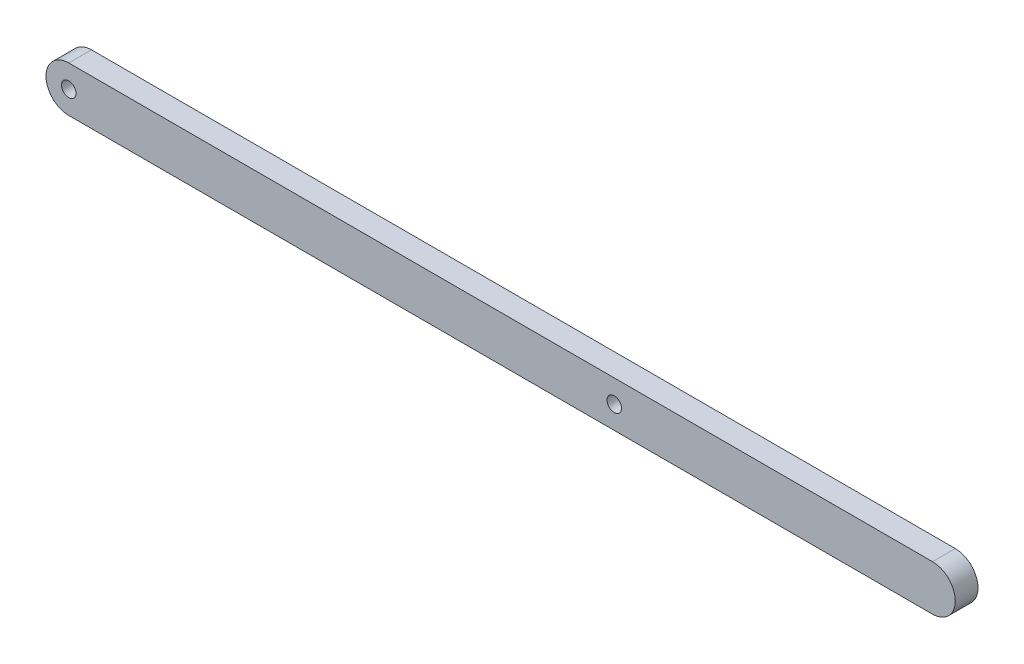
SolidWorks part; units mm, degrees
ref_plane "前视基准面" through (0, 0, 0) normal (0, 0, 1) x (1, 0, 0)
ref_plane "上视基准面" through (0, 0, 0) normal (0, 1, 0) x (1, 0, 0)
ref_plane "右视基准面" through (0, 0, 0) normal (1, 0, 0) x (0, 0, -1)
other "Configuration Table"
sketch "草图1" plane through (0, 0, 0) normal (0, 0, 1) x (1, 0, 0)
  line L0 (0, 0) -> (190, 0) construction
  line L1 (0, 5) -> (190, 5)
  line L2 (0, -5) -> (190, -5)
  arc A0 (0, 5) -> (0, -5) centre (0, 0) ccw
  arc A1 (190, -5) -> (190, 5) centre (190, 0) ccw
  circle A2 centre (120, 0) radius 1.6
  circle A3 centre (0, 0) radius 1.6
  point P3 (95, 0)
  dimension "D3" = 3.2
  dimension "D5" = 3.2
  dimension "D1" = 190
  dimension "D2" = 10
  dimension "D4" = 120
extrude "凸台-拉伸1" add sketch "草图1" along normal blind 5
